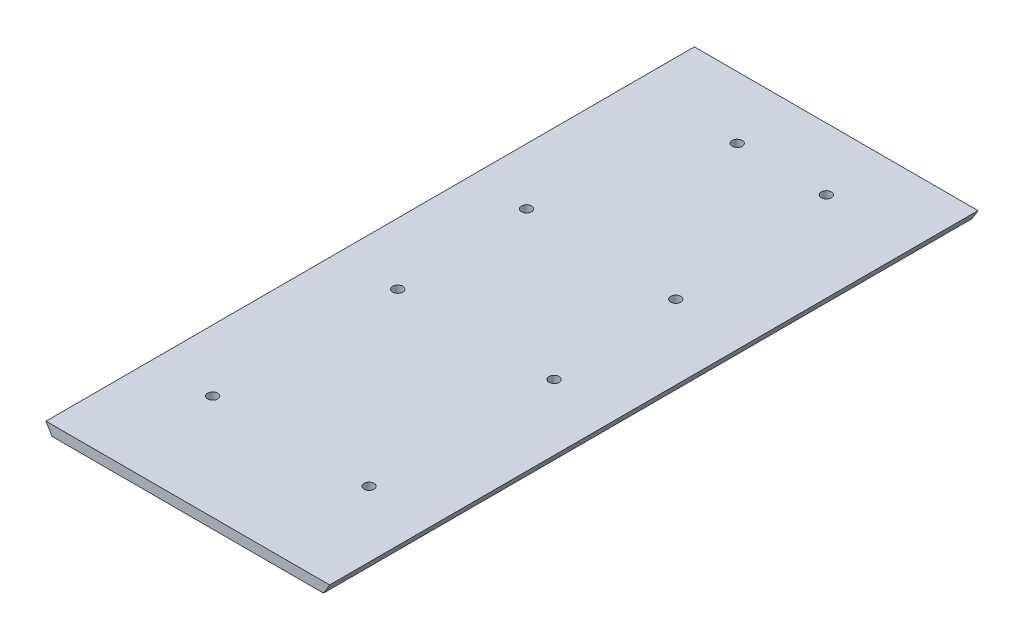
SolidWorks part; units mm, degrees
ref_plane "Front Plane" through (0, 0, 0) normal (0, 0, 1) x (1, 0, 0)
ref_plane "Top Plane" through (0, 0, 0) normal (0, 1, 0) x (1, 0, 0)
ref_plane "Right Plane" through (0, 0, 0) normal (1, 0, 0) x (0, 0, -1)
sketch "Sketch2" plane through (0, 0, 0) normal (0, 0, 1) x (1, 0, 0)
  line L0 (0, -24.5934) -> (0, -27.7938) construction
  line L2 (-44.45, -24.5934) -> (44.45, -24.5934)
  line L3 (42.5223, -27.7938) -> (-42.5223, -27.7938)
  arc A0 (42.5223, -27.7938) -> (44.45, -24.5934) centre (0, 0) ccw
  arc A2 (-44.45, -24.5934) -> (-42.5223, -27.7938) centre (0, 0) ccw
  dimension "D1" = 3.2004
extrude "Boss-Extrude1" add sketch "Sketch2" along normal blind 203.2 contours L2 A0 L3 A2
sketch "Sketch3" plane through (0, -24.5934, 0) normal (0, 1, 0) x (1, 0, 0)
  circle A0 centre (-11.5382, -19.4789) radius 1.5875
  circle A1 centre (16.4018, -19.4789) radius 1.5875
  circle A2 centre (-26.7782, -70.2789) radius 1.5875
  circle A3 centre (21.1379, -71.4219) radius 1.5875
  dimension "D1" = 27.94
  dimension "D2" = 15.24
  dimension "D4" = 47.9298
  dimension "D7" = 3.175
  dimension "D3" = 50.8
  dimension "D5" = 51.943
  dimension "D6" = 4.7362
extrude "Cut-Extrude1" cut sketch "Sketch3" against normal through all contours A1 | A2 | A3 | A0
sketch "Sketch4" plane through (0, -24.5934, 0) normal (0, 1, 0) x (1, 0, 0)
  line L0 (0, 0) -> (0, -203.2) construction
  line L1 (-44.45, 0) -> (44.45, 0) construction
  line L2 (-44.45, -203.2) -> (44.45, -203.2) construction
  circle A0 centre (-25.1524, -112.2534) radius 1.5875
  circle A2 centre (23.8476, -112.2534) radius 1.5875
  circle A3 centre (23.8476, -170.2534) radius 1.5875
  circle A4 centre (-25.1524, -170.2534) radius 1.5875
  dimension "D1" = 3.175
  dimension "D2" = 49
  dimension "D3" = 58
extrude "Cut-Extrude2" cut sketch "Sketch4" against normal through all contours A4 | A3 | A2 | A0
